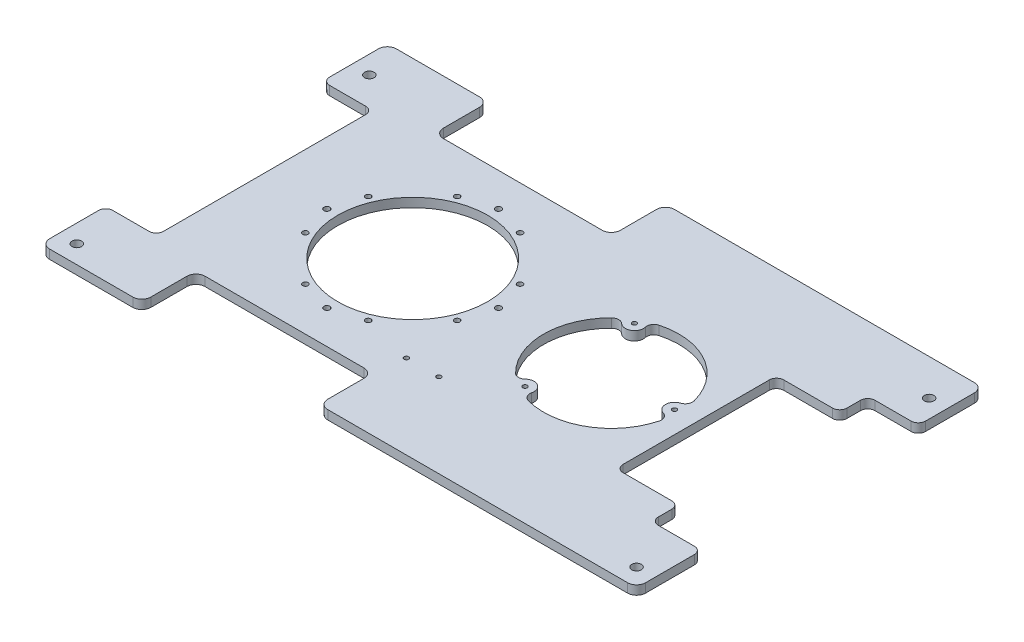
SolidWorks part; units mm, degrees
ref_plane "Front Plane" through (0, 0, 0) normal (0, 0, 1) x (1, 0, 0)
ref_plane "Top Plane" through (0, 0, 0) normal (0, 1, 0) x (1, 0, 0)
ref_plane "Right Plane" through (0, 0, 0) normal (1, 0, 0) x (0, 0, -1)
ref_plane "Plane1" through (0, 0, 0) normal (0, -1, 0) x (1, 0, 0)
sketch "Sketch1" plane through (0, 0, 0) normal (0, -1, 0) x (1, 0, 0)
  line L0 (159, -192) -> (325, -192)
  line L1 (330, -187) -> (330, -160)
  line L2 (326, -156) -> (306, -156)
  line L3 (302, -152) -> (302, -144.5)
  line L4 (298, -140.5) -> (271, -140.5)
  line L5 (267, -136.5) -> (267, -55.5)
  line L6 (271, -51.5) -> (298, -51.5)
  line L7 (302, -47.5) -> (302, -40)
  line L8 (306, -36) -> (326, -36)
  line L9 (330, -32) -> (330, -5)
  line L10 (325, 0) -> (159, 0)
  line L11 (154, -5) -> (154, -25)
  line L12 (149, -30) -> (61, -30)
  line L13 (56, -25) -> (56, -5)
  line L14 (51, 0) -> (5, 0)
  line L15 (0, -5) -> (0, -32)
  line L16 (4, -36) -> (24, -36)
  line L17 (28, -40) -> (28, -152)
  line L18 (24, -156) -> (4, -156)
  line L19 (0, -160) -> (0, -187)
  line L20 (5, -192) -> (51, -192)
  line L21 (56, -187) -> (56, -167)
  line L22 (61, -162) -> (149, -162)
  line L23 (154, -167) -> (154, -187)
  arc A0 (210.2252, -59.7964) -> (256.2407, -86.3634) centre (220, -96) cw
  arc A1 (256.2407, -86.3634) -> (253.5417, -91.2174) centre (252.375, -87.3913) cw
  arc A2 (253.5417, -91.2174) -> (253.5417, -100.7826) centre (255, -96) ccw
  arc A3 (253.5417, -100.7826) -> (256.2407, -105.6366) centre (252.375, -104.6087) cw
  arc A4 (256.2407, -105.6366) -> (210.2252, -132.2036) centre (220, -96) cw
  arc A5 (210.2252, -132.2036) -> (207.371, -127.4392) centre (211.2678, -128.3419) cw
  arc A6 (207.371, -127.4392) -> (199.0873, -122.6566) centre (202.5, -126.3109) ccw
  arc A7 (199.0873, -122.6566) -> (193.5341, -122.5671) centre (196.3572, -119.7332) cw
  arc A8 (193.5341, -122.5671) -> (193.5341, -69.4329) centre (220, -96) cw
  arc A9 (193.5341, -69.4329) -> (199.0873, -69.3434) centre (196.3572, -72.2668) cw
  arc A10 (199.0873, -69.3434) -> (207.371, -64.5608) centre (202.5, -65.6891) ccw
  arc A11 (207.371, -64.5608) -> (210.2252, -59.7964) centre (211.2678, -63.6581) cw
  circle A12 centre (92.5879, -138.0365) radius 1.5
  circle A13 centre (127.4121, -138.0365) radius 1.5
  circle A14 centre (152.0365, -113.4121) radius 1.5
  circle A15 centre (152.0365, -78.5879) radius 1.5
  circle A16 centre (127.4121, -53.9635) radius 1.5
  circle A17 centre (92.5879, -53.9635) radius 1.5
  circle A18 centre (67.9635, -78.5879) radius 1.5
  circle A19 centre (67.9635, -113.4121) radius 1.5
  circle A20 centre (110, -96) radius 41.5
  circle A21 centre (320, -172) radius 2.65
  circle A22 centre (320, -10) radius 2.65
  circle A23 centre (10, -10) radius 2.65
  circle A24 centre (10, -172) radius 2.65
  circle A25 centre (110, -143.5) radius 1.65
  circle A26 centre (62.5, -96) radius 1.65
  circle A27 centre (110, -48.5) radius 1.65
  circle A28 centre (157.5, -96) radius 1.65
  circle A29 centre (202.5, -126.3109) radius 1.25
  circle A30 centre (255, -96) radius 1.25
  circle A31 centre (202.5, -65.6891) radius 1.25
  circle A32 centre (156, -46.5) radius 1.25
  circle A33 centre (174, -46.5) radius 1.25
  arc A34 (325, -192) -> (330, -187) centre (325, -187) ccw
  arc A35 (330, -160) -> (326, -156) centre (326, -160) ccw
  arc A36 (306, -156) -> (302, -152) centre (306, -152) cw
  arc A37 (302, -144.5) -> (298, -140.5) centre (298, -144.5) ccw
  arc A38 (271, -140.5) -> (267, -136.5) centre (271, -136.5) cw
  arc A39 (267, -55.5) -> (271, -51.5) centre (271, -55.5) cw
  arc A40 (298, -51.5) -> (302, -47.5) centre (298, -47.5) ccw
  arc A41 (302, -40) -> (306, -36) centre (306, -40) cw
  arc A42 (326, -36) -> (330, -32) centre (326, -32) ccw
  arc A43 (330, -5) -> (325, 0) centre (325, -5) ccw
  arc A44 (159, 0) -> (154, -5) centre (159, -5) ccw
  arc A45 (154, -25) -> (149, -30) centre (149, -25) cw
  arc A46 (61, -30) -> (56, -25) centre (61, -25) cw
  arc A47 (56, -5) -> (51, 0) centre (51, -5) ccw
  arc A48 (5, 0) -> (0, -5) centre (5, -5) ccw
  arc A49 (0, -32) -> (4, -36) centre (4, -32) ccw
  arc A50 (24, -36) -> (28, -40) centre (24, -40) cw
  arc A51 (28, -152) -> (24, -156) centre (24, -152) cw
  arc A52 (4, -156) -> (0, -160) centre (4, -160) ccw
  arc A53 (0, -187) -> (5, -192) centre (5, -187) ccw
  arc A54 (51, -192) -> (56, -187) centre (51, -187) ccw
  arc A55 (56, -167) -> (61, -162) centre (61, -167) cw
  arc A56 (149, -162) -> (154, -167) centre (149, -167) cw
  arc A57 (154, -187) -> (159, -192) centre (159, -187) ccw
extrude "Boss-Extrude1" add sketch "Sketch1" against normal blind 5
